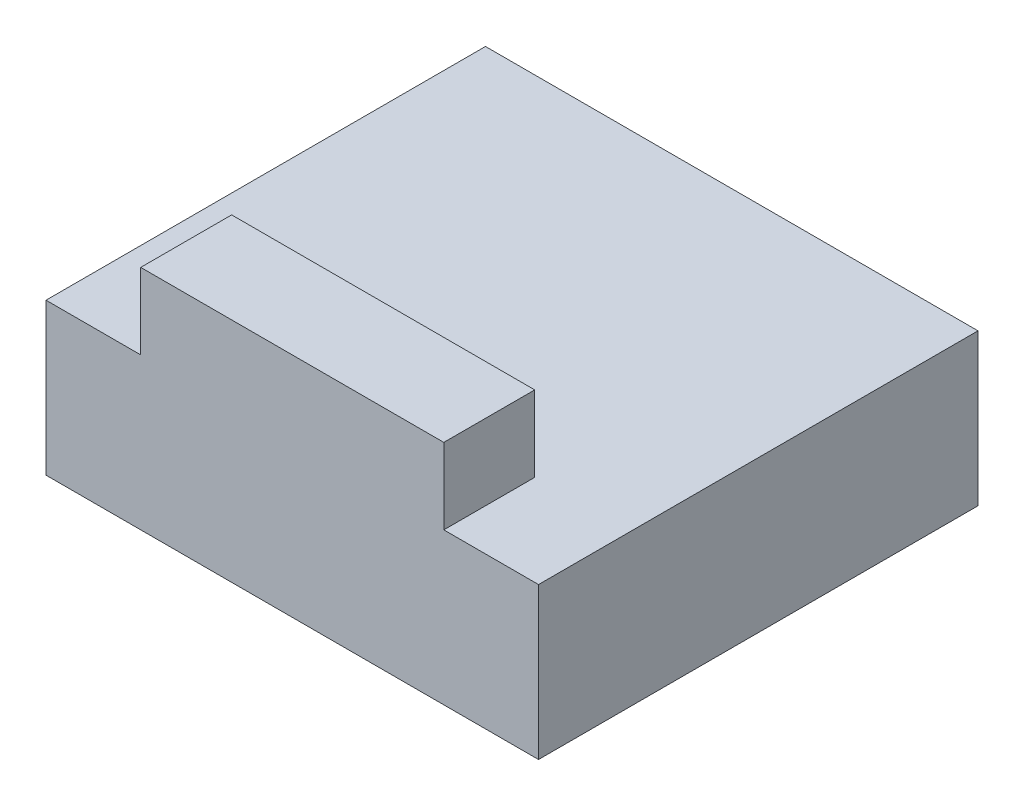
SolidWorks part; units mm, degrees
ref_plane "Front Plane" through (0, 0, 0) normal (0, 0, 1) x (1, 0, 0)
ref_plane "Top Plane" through (0, 0, 0) normal (0, 1, 0) x (1, 0, 0)
ref_plane "Right Plane" through (0, 0, 0) normal (1, 0, 0) x (0, 0, -1)
sketch "Sketch1" plane through (0, 0, 0) normal (0, 1, 0) x (1, 0, 0)
  line L1 (32.5, -29) -> (-32.5, -29)
  line L2 (32.5, -29) -> (32.5, 29)
  line L3 (32.5, 29) -> (-32.5, 29)
  line L4 (-32.5, -29) -> (-32.5, 29)
  line L5 (32.5, -29) -> (-32.5, 29) construction
  line L6 (32.5, 29) -> (-32.5, -29) construction
  point P0 (0, 0)
  dimension "D1" = 58
  dimension "D2" = 65
extrude "Boss-Extrude1" add sketch "Sketch1" along normal blind 20
sketch "Sketch2" plane through (0, 0, 0) normal (0, -1, 0) x (1, 0, 0)
  line L0 (-32.5, 29) -> (32.5, 29) construction
  line L1 (-20, 29) -> (20, 29)
  line L2 (-20, 29) -> (-20, 17)
  line L3 (-20, 17) -> (20, 17)
  line L4 (20, 29) -> (20, 17)
  point P6 (0, 17)
  dimension "D1" = 40
  dimension "D2" = 12
extrude "Boss-Extrude2" add sketch "Sketch2" against normal blind 30
